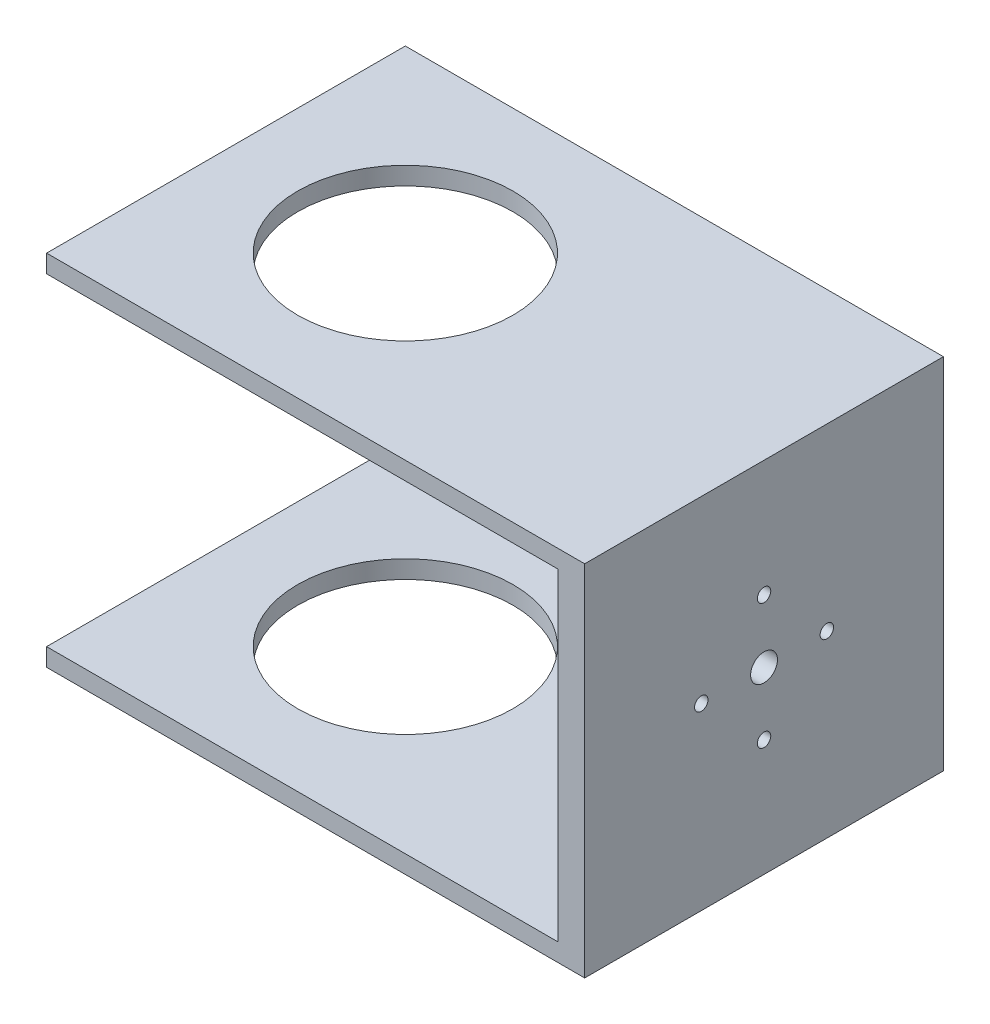
SolidWorks part; units mm, degrees
ref_plane "前视基准面" through (0, 0, 0) normal (0, 0, 1) x (1, 0, 0)
ref_plane "上视基准面" through (0, 0, 0) normal (0, 1, 0) x (1, 0, 0)
ref_plane "右视基准面" through (0, 0, 0) normal (1, 0, 0) x (0, 0, -1)
sketch "草图1" plane through (0, 0, 0) normal (0, 0, 1) x (1, 0, 0)
  line L1 (0, 0) -> (60, 0)
  line L2 (0, 0) -> (0, 40)
  line L3 (0, 40) -> (60, 40)
  line L4 (60, 0) -> (60, 40)
  dimension "D1" = 60
  dimension "D2" = 40
extrude "凸台-拉伸1" add sketch "草图1" along normal blind 40
sketch "草图2" plane through (0, 0, 0) normal (-1, 0, 0) x (0, 0, 1)
  line L0 (0, 40) -> (0, 0) construction
  line L1 (0, 38) -> (40, 38)
  line L2 (0, 38) -> (0, 2)
  line L3 (0, 2) -> (40, 2)
  line L4 (40, 38) -> (40, 2)
  line L5 (40, 40) -> (40, 0) construction
  line L6 (40, 40) -> (0, 40) construction
  line L7 (40, 0) -> (0, 0) construction
  dimension "D1" = 2
  dimension "D2" = 2
extrude "切除-拉伸1" cut sketch "草图2" against normal blind 57
sketch "草图3" plane through (60, 0, 0) normal (1, 0, 0) x (0, 0, -1)
  line L0 (-40, 40) -> (0, 40) construction
  line L1 (0, 0) -> (0, 40) construction
  circle A0 centre (-20, 20) radius 1.5
  dimension "D1" = 3
  dimension "D2" = 20
  dimension "D3" = 20
extrude "切除-拉伸2" cut sketch "草图3" against normal up to next
sketch "草图4" plane through (60, 0, 0) normal (1, 0, 0) x (0, 0, -1)
  line L0 (-40, 40) -> (0, 40) construction
  line L1 (-40, 0) -> (-40, 40) construction
  circle A0 centre (-20, 27) radius 0.75
  circle A2 centre (-13, 20) radius 0.75
  circle A3 centre (-20, 13) radius 0.75
  circle A4 centre (-27, 20) radius 0.75
  point P15 (-20, 20)
  dimension "D1" = 4
  dimension "D2" = 1.5
  dimension "D3" = 14
  dimension "D4" = 13
  dimension "D5" = 20
  dimension "D6" = 13
extrude "切除-拉伸3" cut sketch "草图4" against normal blind 38
sketch "草图5" plane through (0, 40, 0) normal (0, 1, 0) x (1, 0, 0)
  line L0 (60, -40) -> (60, 0) construction
  line L1 (60, 0) -> (0, 0) construction
  circle A0 centre (20, -20) radius 12
  dimension "D1" = 24
  dimension "D2" = 40
  dimension "D3" = 20
extrude "切除-拉伸4" cut sketch "草图5" against normal through all
